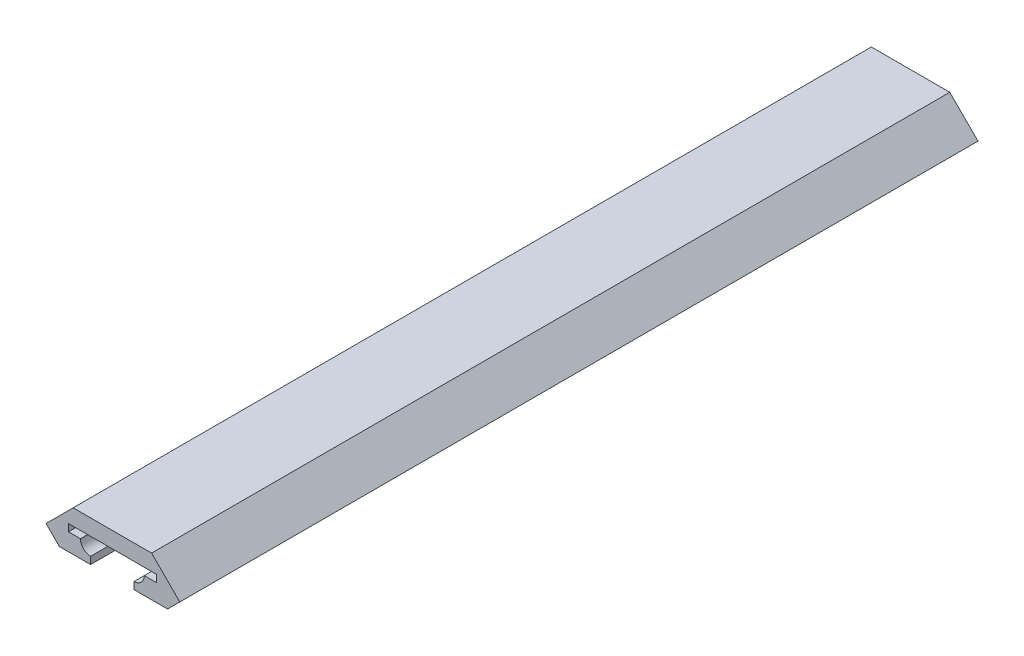
SolidWorks part; units mm, degrees
ref_plane "Front Plane" through (0, 0, 0) normal (0, 0, 1) x (1, 0, 0)
ref_plane "Top Plane" through (0, 0, 0) normal (0, 1, 0) x (1, 0, 0)
ref_plane "Right Plane" through (0, 0, 0) normal (1, 0, 0) x (0, 0, -1)
sketch "Sketch1" plane through (0, 0, 0) normal (0, 0, 1) x (1, 0, 0)
  line L0 (0, 0) -> (11, 0)
  line L1 (11, 0) -> (11, -0.9)
  line L2 (11, -0.9) -> (9.5, -0.9)
  line L3 (9.5, -0.9) -> (8.23, -0.9) construction
  line L4 (8.23, -0.9) -> (8.23, -2.17) construction
  line L5 (8.23, -2.17) -> (8.23, -3.07)
  line L6 (0, 0) -> (0, -0.9)
  line L7 (0, -0.9) -> (1.5, -0.9)
  line L8 (1.5, -0.9) -> (2.77, -0.9) construction
  line L9 (2.77, -0.9) -> (2.77, -2.17) construction
  line L10 (2.77, -2.17) -> (2.77, -3.07)
  line L11 (5.5, 0) -> (5.5, 6.9142) construction
  line L12 (5.5, 6.9142) -> (17.5643, -5.1501) construction
  line L13 (5.5, 6.9142) -> (-4.4773, -3.0631) construction
  line L14 (10.4142, 2) -> (0.5858, 2) construction
  line L15 (2.77, -3.07) -> (-4.4842, -3.07) construction
  line L16 (2.77, -3.07) -> (15.4842, -3.07) construction
  line L17 (8.23, -3.07) -> (12.4153, -3.07)
  line L18 (12.4153, -3.07) -> (13.9497, -1.5355) construction
  line L19 (12.4153, -3.07) -> (13.9497, -1.5355)
  line L20 (13.9497, -1.5355) -> (10.4142, 2)
  line L21 (10.4142, 2) -> (0.5858, 2)
  line L22 (0.5858, 2) -> (-2.8147, -1.4005)
  line L23 (-2.8147, -1.4005) -> (-1.1453, -3.07)
  line L24 (-1.1453, -3.07) -> (2.77, -3.07)
  arc A0 (1.5, -0.9) -> (2.77, -2.17) centre (2.77, -0.9) ccw
  arc A1 (9.5, -0.9) -> (8.23, -2.17) centre (8.23, -0.9) cw
  point P24 (5.5, 6.9962)
  dimension "D1" = 11
  dimension "D2" = 0.9
  dimension "D3" = 1.5
  dimension "D4" = 1.5
  dimension "D5" = 1.27
  dimension "D6" = 1.27
  dimension "D7" = 1.27
  dimension "D8" = 0.9
  dimension "D9" = 45
  dimension "D10" = 1
  dimension "D11" = 45
  dimension "D12" = 2
  dimension "D13" = 5
extrude "Boss-Extrude1" add sketch "Sketch1" along normal blind 100
